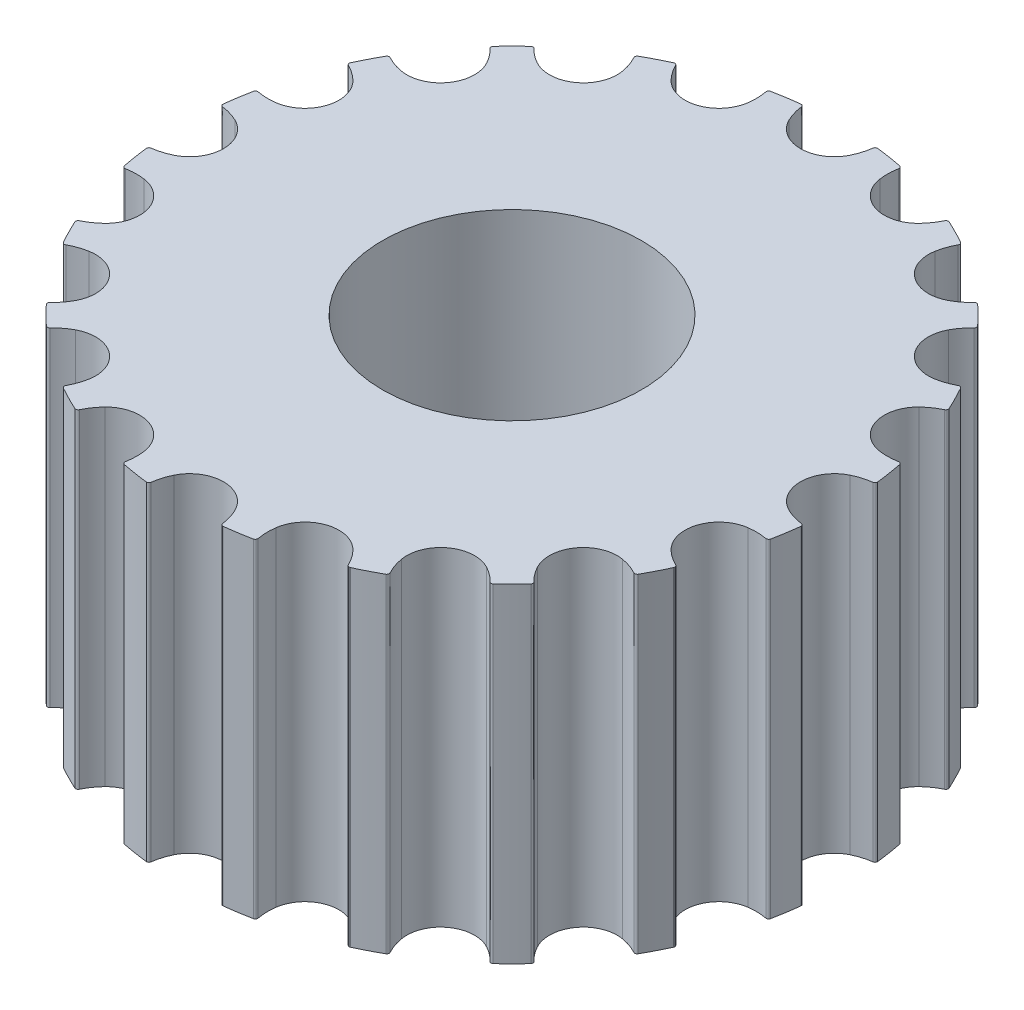
SolidWorks part; units mm, degrees
ref_plane "Front Plane" through (0, 0, 0) normal (0, 0, 1) x (1, 0, 0)
ref_plane "Top Plane" through (0, 0, 0) normal (0, 1, 0) x (1, 0, 0)
ref_plane "Right Plane" through (0, 0, 0) normal (1, 0, 0) x (0, 0, -1)
other "Default"
sketch "Sketch1" plane through (0, 0, 0) normal (0, 1, 0) x (1, 0, 0)
  circle A0 centre (0, 0) radius 2.5
  circle A1 centre (0, 0) radius 6.365
  dimension "ID" = 5
  dimension "OD" = 12.73
extrude "Boss-Extrude1" add sketch "Sketch1" along normal mid plane 6.35
sketch "Sketch2" plane through (0, 3.175, 0) normal (0, 1, 0) x (1, 0, 0)
  line L0 (0, 27.6626) -> (0, 29.4664) construction
  line L1 (-0.4, 6.4218) -> (0.4, 6.4218) construction
  line L2 (-0.8476, 6.4218) -> (1.0421, 6.4218) construction
  arc A0 (-0.4989, 5.9836) -> (0.4989, 5.9836) centre (0, 6.2268) ccw construction
  arc A1 (-0.4989, 5.9836) -> (-0.5915, 6.2914) centre (0.4, 6.4218) cw construction
  arc A2 (-0.5915, 6.2914) -> (-0.7402, 6.4218) centre (-0.7402, 6.2718) ccw construction
  arc A3 (0.4989, 5.9836) -> (0.5915, 6.2914) centre (-0.4, 6.4218) ccw construction
  arc A4 (0.5915, 6.2914) -> (0.7402, 6.4218) centre (0.7402, 6.2718) cw construction
  arc A6 (0.6906, 6.2783) -> (0.7402, 6.3218) centre (0.7402, 6.2718) cw
  arc A7 (0.5888, 5.9398) -> (0.6906, 6.2783) centre (-0.4, 6.4218) ccw
  arc A8 (-0.5888, 5.9398) -> (0.5888, 5.9398) centre (0, 6.2268) ccw
  arc A9 (-0.5888, 5.9398) -> (-0.6906, 6.2783) centre (0.4, 6.4218) cw
  arc A10 (-0.6906, 6.2783) -> (-0.7402, 6.3218) centre (-0.7402, 6.2718) ccw
  circle A11 centre (0, 0) radius 6.365 construction
  arc A12 (-0.7402, 6.3218) -> (0.7402, 6.3218) centre (0, 0) cw
  point P13 (0, 6.4218)
  point P15 (0, 5.6718)
  dimension "D1" = 0.555
  dimension "D2" = 1
  dimension "D3" = 0.15
  dimension "D4" = 0.4
  dimension "D5" = 0.75
  dimension "D6" = 0.1
extrude "Cut-Extrude1" cut sketch "Sketch2" against normal through all
pattern_circular "CirPattern1" count 20 over 360 about axis through (0, 0, 0) along (0, 1, 0) of "Cut-Extrude1"
